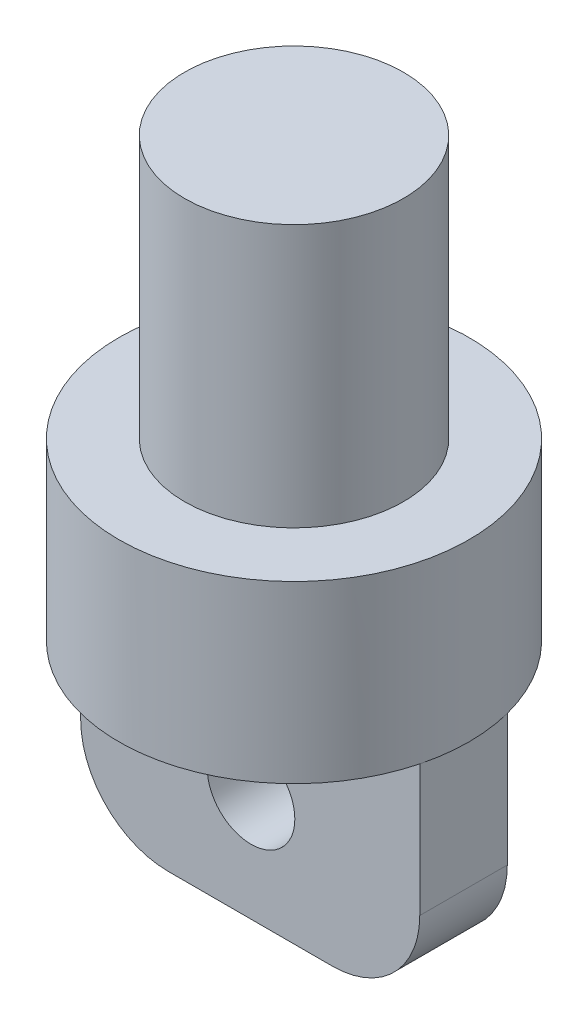
SolidWorks part; units mm, degrees
ref_plane "Front Plane" through (0, 0, 0) normal (0, 0, 1) x (1, 0, 0)
ref_plane "Top Plane" through (0, 0, 0) normal (0, 1, 0) x (1, 0, 0)
ref_plane "Right Plane" through (0, 0, 0) normal (1, 0, 0) x (0, 0, -1)
sketch "Sketch1" plane through (0, 0, 0) normal (0, 1, 0) x (1, 0, 0)
  circle A0 centre (0, 0) radius 50.8
  dimension "D1" = 101.6
extrude "Boss-Extrude1" add sketch "Sketch1" along normal blind 50.8
sketch "Sketch2" plane through (0, 50.8, 0) normal (0, 1, 0) x (1, 0, 0)
  circle A0 centre (0, 0) radius 31.75
  dimension "D1" = 63.5
extrude "Boss-Extrude2" add sketch "Sketch2" along normal blind 76.2
sketch "Sketch3" plane through (0, 0, 0) normal (0, -1, 0) x (1, 0, 0)
  line L1 (-49.1869, -12.7) -> (49.1869, -12.7)
  line L2 (-49.1869, -12.7) -> (-49.1869, 12.7)
  line L3 (-49.1869, 12.7) -> (49.1869, 12.7)
  line L4 (49.1869, -12.7) -> (49.1869, 12.7)
  line L5 (-49.1869, -12.7) -> (49.1869, 12.7) construction
  line L6 (-49.1869, 12.7) -> (49.1869, -12.7) construction
  circle A0 centre (0, 0) radius 50.8 construction
  point P0 (0, 0)
  dimension "D1" = 25.4
extrude "Boss-Extrude3" add sketch "Sketch3" along normal blind 63.5
sketch "Sketch4" plane through (0, 0, 12.7) normal (0, 0, 1) x (1, 0, 0)
  circle A0 centre (0.244, -31.9671) radius 12.7
extrude "Cut-Extrude1" cut sketch "Sketch4" against normal through all contours A0
fillet "Fillet1" radius 25.4 1 edges at (-49.1869, -63.5, 0)
fillet "Fillet2" radius 25.4 1 edges at (49.1869, -63.5, 0)
